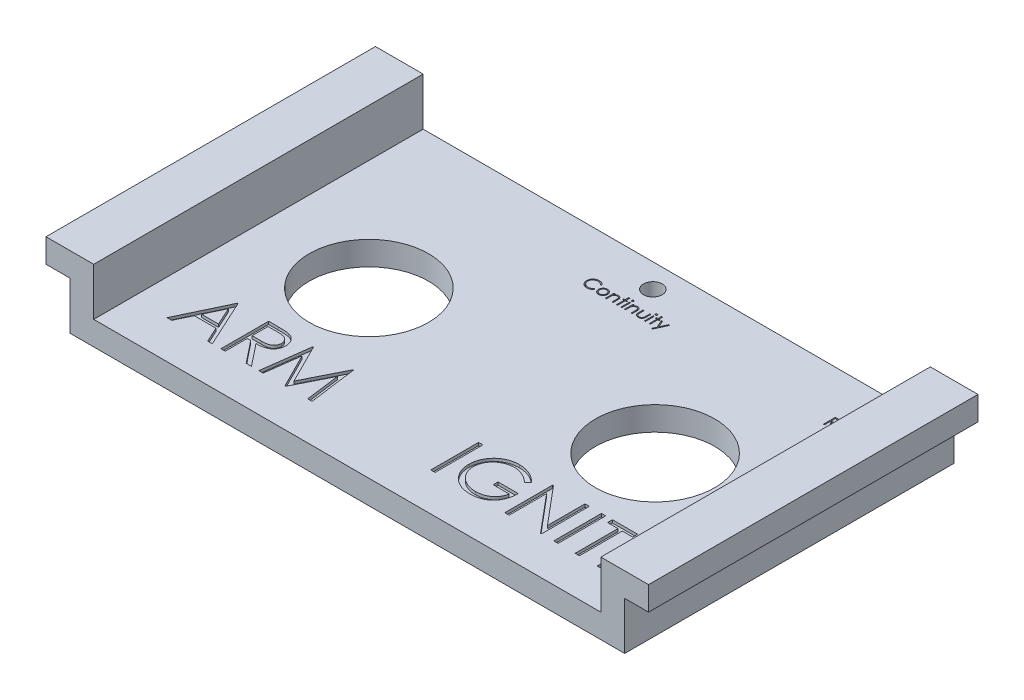
SolidWorks part; units mm, degrees
ref_plane "Front Plane" through (0, 0, 0) normal (0, 0, 1) x (1, 0, 0)
ref_plane "Top Plane" through (0, 0, 0) normal (0, 1, 0) x (1, 0, 0)
ref_plane "Right Plane" through (0, 0, 0) normal (1, 0, 0) x (0, 0, -1)
sketch "Çizim1" plane through (0, 0, 0) normal (0, 1, 0) x (1, 0, 0)
  line L1 (-73.85, -43.85) -> (73.85, -43.85)
  line L2 (-73.85, -43.85) -> (-73.85, 43.85)
  line L3 (-73.85, 43.85) -> (73.85, 43.85)
  line L4 (73.85, -43.85) -> (73.85, 43.85)
  line L5 (-73.85, -43.85) -> (73.85, 43.85) construction
  line L6 (-73.85, 43.85) -> (73.85, -43.85) construction
  point P0 (0, 0)
  dimension "D1" = 147.7
  dimension "D2" = 87.7
extrude "Yükseklik-Ekstrüzyon1" add sketch "Çizim1" along normal blind 6.35
sketch "Çizim2" plane through (-73.85, 0, 0) normal (-1, 0, 0) x (0, 0, 1)
  line L1 (-43.85, 6.35) -> (43.85, 6.35)
  line L2 (-43.85, 6.35) -> (-43.85, 19.05)
  line L3 (-43.85, 19.05) -> (43.85, 19.05)
  line L4 (43.85, 6.35) -> (43.85, 19.05)
  dimension "D1" = 87.7
  dimension "D2" = 12.7
extrude "Yükseklik-Ekstrüzyon2" add sketch "Çizim2" against normal blind 6.35
sketch "Çizim3" plane through (73.85, 0, 0) normal (1, 0, 0) x (0, 0, -1)
  line L1 (-43.85, 6.35) -> (43.85, 6.35)
  line L2 (-43.85, 6.35) -> (-43.85, 19.05)
  line L3 (-43.85, 19.05) -> (43.85, 19.05)
  line L4 (43.85, 6.35) -> (43.85, 19.05)
extrude "Yükseklik-Ekstrüzyon3" add sketch "Çizim3" against normal blind 6.35
sketch "Çizim4" plane through (73.85, 0, 0) normal (1, 0, 0) x (0, 0, -1)
  line L0 (43.85, 19.05) -> (43.85, 0) construction
  line L1 (-43.85, 19.05) -> (43.85, 19.05)
  line L2 (-43.85, 19.05) -> (-43.85, 12.7)
  line L3 (-43.85, 12.7) -> (43.85, 12.7)
  line L4 (43.85, 19.05) -> (43.85, 12.7)
  dimension "D1" = 6.35
sketch "Çizim6" plane through (-73.85, 0, 0) normal (-1, 0, 0) x (0, 0, 1)
  line L1 (-43.85, 19.05) -> (43.85, 19.05)
  line L2 (-43.85, 19.05) -> (-43.85, 12.7)
  line L3 (-43.85, 12.7) -> (43.85, 12.7)
  line L4 (43.85, 19.05) -> (43.85, 12.7)
extrude "Yükseklik-Ekstrüzyon4" add sketch "Çizim6" along normal blind 6.35
extrude "Yükseklik-Ekstrüzyon5" add sketch "Çizim4" along normal blind 6.35
sketch "Çizim7" plane through (0, 6.35, 0) normal (0, 1, 0) x (1, 0, 0)
  circle A0 centre (-38.1, 0) radius 15.875
  dimension "D1" = 31.75
  dimension "D2" = 38.1
extrude "Kes-Ekstrüzyon1" cut sketch "Çizim7" against normal blind 6.35
sketch "Çizim8" plane through (0, 6.35, 0) normal (0, 1, 0) x (1, 0, 0)
  circle A0 centre (38.1, 0) radius 15.875
  dimension "D1" = 31.75
  dimension "D2" = 38.1
extrude "Kes-Ekstrüzyon2" cut sketch "Çizim8" against normal blind 6.35
sketch "Çizim9" plane through (0, 6.35, 0) normal (0, 1, 0) x (1, 0, 0)
  line L0 (67.5, 43.85) -> (-67.5, 43.85) construction
  line L1 (67.5, 43.85) -> (67.5, -43.85) construction
  circle A0 centre (61.15, 37.5) radius 2.5
  dimension "D1" = 5
  dimension "D2" = 6.35
  dimension "D3" = 6.35
extrude "Kes-Ekstrüzyon3" cut sketch "Çizim9" against normal blind 6.35
sketch "Çizim10" plane through (0, 6.35, 0) normal (0, 1, 0) x (1, 0, 0)
  line L0 (67.5, 43.85) -> (-67.5, 43.85) construction
  circle A0 centre (0, 37.5) radius 2.5
  dimension "D1" = 5
  dimension "D2" = 6.35
extrude "Kes-Ekstrüzyon4" cut sketch "Çizim10" against normal blind 6.35
sketch "Çizim11" plane through (0, 6.35, 0) normal (0, 1, 0) x (1, 0, 0)
  line L0 (67.5, 43.85) -> (-67.5, 43.85) construction
  text T0 "Continuity"
  point P1 (-8.2403, 30.1034)
  point P2 (-11.49, 30.0002)
  point P3 (-10.7905, 29.3723)
  point P4 (0, 0)
  point P5 (0, 0)
  point P6 (0, 0)
  point P7 (-11.5692, 29.3723)
  point P8 (-11.0739, 29.375)
  dimension "D1" = 14.732
extrude "Kes-Ekstrüzyon5" cut sketch "Çizim11" against normal blind 0.762
sketch "Çizim12" plane through (0, 6.35, 0) normal (0, 1, 0) x (1, 0, 0)
  line L0 (67.5, 43.85) -> (-67.5, 43.85) construction
  text T0 "Radio"
  point P1 (53.5362, 30.3997)
  point P2 (53.388, 29.1881)
  dimension "D1" = 14.732
extrude "Kes-Ekstrüzyon6" cut sketch "Çizim12" against normal blind 0.762
sketch "Çizim13" plane through (0, 6.35, 0) normal (0, 1, 0) x (1, 0, 0)
  line L0 (-67.5, -43.85) -> (67.5, -43.85) construction
  text T0 "ARM" font "Century Gothic" height 12.7
  point P2 (10.6618, -32.2171)
  point P3 (0, 0)
  point P4 (0, 0)
  dimension "D1" = 10.16
sketch "Çizim14" plane through (0, 6.35, 0) normal (0, 1, 0) x (1, 0, 0)
  line L0 (-67.5, -43.85) -> (67.5, -43.85) construction
  text T0 "IGNITE" font "Century Gothic" height 12.7
  point P3 (17.2727, -31.15)
  point P4 (8.6813, -31.15)
  point P5 (0, 0)
  point P6 (9.5697, -33.69)
  point P7 (9.8865, -33.69)
  point P8 (10.458, -33.69)
  dimension "D1" = 10.16
extrude "Kes-Ekstrüzyon7" cut sketch "Çizim13" against normal blind 0.762
extrude "Kes-Ekstrüzyon8" cut sketch "Çizim14" against normal blind 0.762
